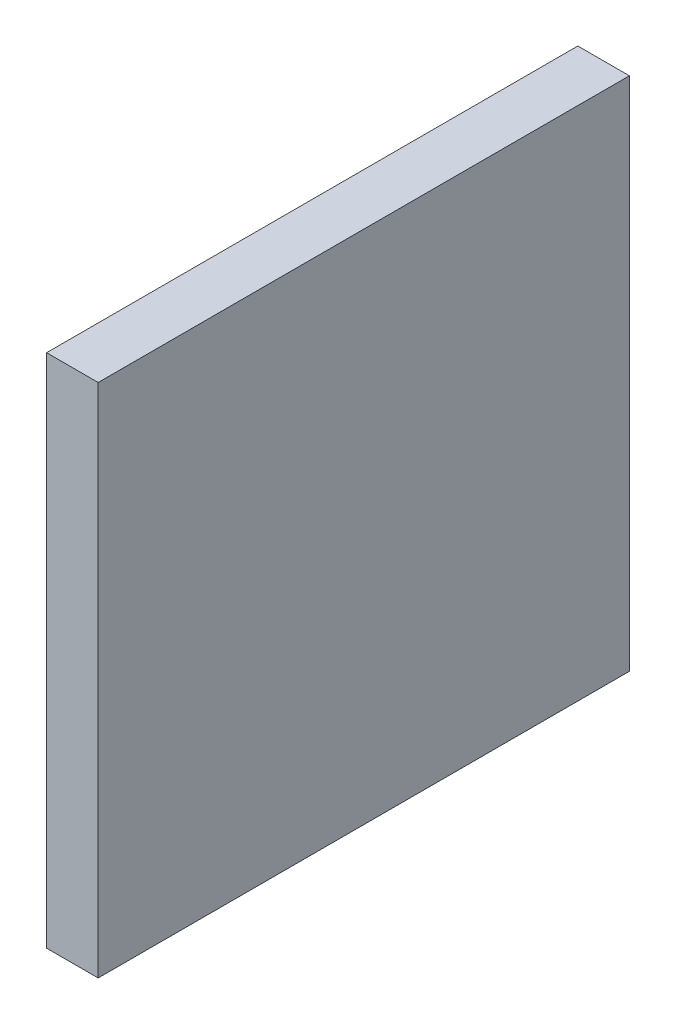
SolidWorks part; units mm, degrees
ref_plane "Front Plane" through (0, 0, 0) normal (0, 0, 1) x (1, 0, 0)
ref_plane "Top Plane" through (0, 0, 0) normal (0, 1, 0) x (1, 0, 0)
ref_plane "Right Plane" through (0, 0, 0) normal (1, 0, 0) x (0, 0, -1)
sketch "Sketch1" plane through (0, 0, 0) normal (1, 0, 0) x (0, 0, -1)
  line L1 (-5.15, 5) -> (5.15, 5)
  line L2 (-5.15, 5) -> (-5.15, -5)
  line L3 (-5.15, -5) -> (5.15, -5)
  line L4 (5.15, 5) -> (5.15, -5)
  line L5 (-5.15, 5) -> (5.15, -5) construction
  line L6 (-5.15, -5) -> (5.15, 5) construction
  point P0 (0, 0)
  dimension "D1" = 10
  dimension "D2" = 10.3
extrude "Boss-Extrude1" add sketch "Sketch1" along normal blind 1
